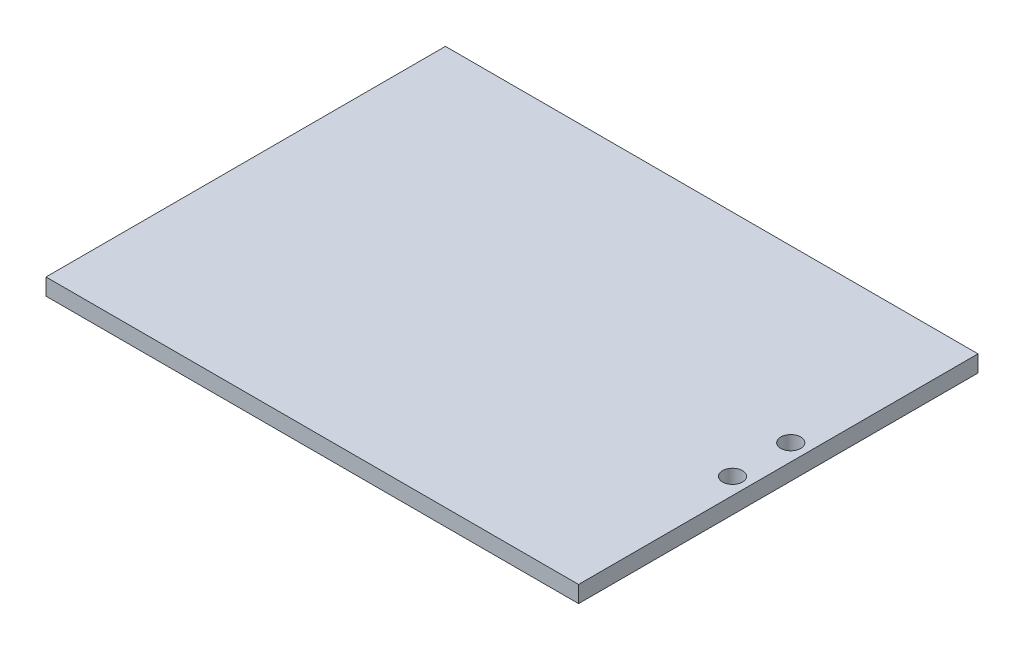
SolidWorks part; units mm, degrees
material "ABS PC"
ref_plane "Front Plane" through (0, 0, 0) normal (0, 0, 1) x (1, 0, 0)
ref_plane "Top Plane" through (0, 0, 0) normal (0, 1, 0) x (1, 0, 0)
ref_plane "Right Plane" through (0, 0, 0) normal (1, 0, 0) x (0, 0, -1)
sketch "Sketch1" plane through (0, 0, 0) normal (0, 1, 0) x (1, 0, 0)
  line L1 (-50.8, 38.1) -> (50.8, 38.1)
  line L2 (-50.8, 38.1) -> (-50.8, -38.1)
  line L3 (-50.8, -38.1) -> (50.8, -38.1)
  line L4 (50.8, 38.1) -> (50.8, -38.1)
  line L5 (-50.8, 38.1) -> (50.8, -38.1) construction
  line L6 (-50.8, -38.1) -> (50.8, 38.1) construction
  point P0 (0, 0)
  dimension "D1" = 101.6
  dimension "D2" = 76.2
extrude "Boss-Extrude1" add sketch "Sketch1" along normal blind 3.175
hole_wizard "#6 Clearance Hole1" positions "Sketch2" profile "Sketch3" hole size "#6" standard "ANSI Inch"
sketch "Sketch2" plane through (0, 3.175, 0) normal (0, 1, 0) x (1, 0, 0)
  line L0 (50.8, -38.1) -> (50.8, 38.1) construction
  point P0 (47.625, 5.5562)
  point P2 (47.625, -5.5562)
  dimension "D1" = 11.1125
  dimension "D2" = 5.5562
  dimension "D3" = 3.175
sketch "Sketch3" plane through (47.625, 3.175, -5.5562) normal (1, 0, 0) x (0, 0, 1)
  line L0 (0, 0) -> (0, 13.8408)
  line L1 (0, 13.8408) -> (1.8986, 12.7)
  line L2 (1.8986, 12.7) -> (1.8986, 0)
  line L5 (1.8986, 0) -> (0, 0)
  line L10 (0, 13.8408) -> (-1.8986, 12.7) construction
  line L11 (0, -6.35) -> (0, 107.95) construction
  dimension "Hole Dia." = 3.7973
  dimension "Hole Depth" = 12.7
  dimension "Drill Angle" = 118
